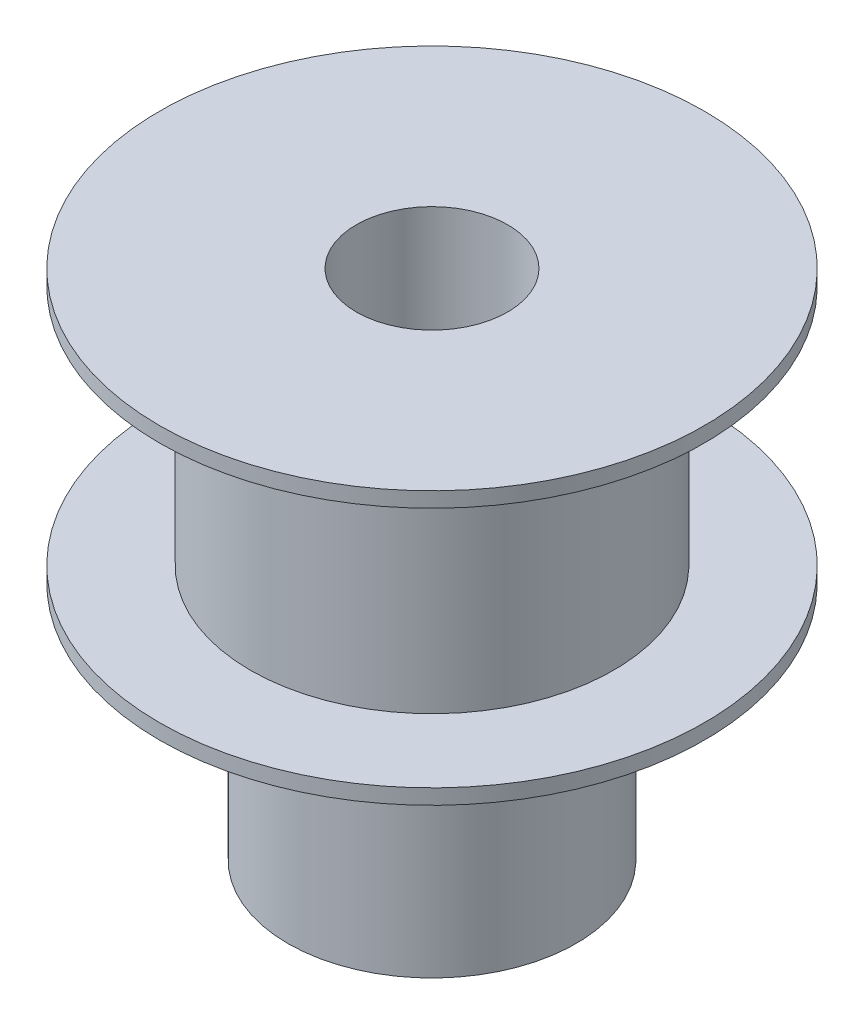
SolidWorks part; units mm, degrees
material "1060 Alloy"
ref_plane "Front Plane" through (0, 0, 0) normal (0, 0, 1) x (1, 0, 0)
ref_plane "Top Plane" through (0, 0, 0) normal (0, 1, 0) x (1, 0, 0)
ref_plane "Right Plane" through (0, 0, 0) normal (1, 0, 0) x (0, 0, -1)
sketch "Sketch1" plane through (0, 0, 0) normal (0, 1, 0) x (1, 0, 0)
  circle A0 centre (0, 0) radius 2.5
  circle A1 centre (0, 0) radius 4.7625
  dimension "D1" = 5
  dimension "D2" = 9.525
extrude "Boss-Extrude1" add sketch "Sketch1" along normal mid plane 7.9375
sketch "Sketch2" plane through (0, 3.9688, 0) normal (0, 1, 0) x (1, 0, 0)
  circle A0 centre (0, 0) radius 2.5
  circle A1 centre (0, 0) radius 9
  circle A2 centre (0, 0) radius 2.5 construction
  dimension "D1" = 18
extrude "Boss-Extrude2" add sketch "Sketch2" along normal blind 9
sketch "Sketch3" plane through (0, 0, 0) normal (1, 0, 0) x (0, 0, -1)
  line L0 (9, 3.9688) -> (9, 12.9688) construction
  line L1 (9, 12.4687) -> (6, 12.4687)
  line L2 (9, 12.4687) -> (9, 4.4688)
  line L3 (9, 4.4688) -> (6, 4.4688)
  line L4 (6, 12.4687) -> (6, 4.4688)
  line L5 (-9, 8.4688) -> (9, 8.4688) construction
  line L6 (-9, 12.9688) -> (-9, 3.9688) construction
  line L7 (9, 12.9688) -> (-9, 12.9688) construction
  point P6 (9, 8.4688)
  dimension "D1" = 0.5
  dimension "D2" = 3
revolve "Cut-Revolve1" cut sketch "Sketch3" angle 360 about axis through (0, 3.9688, 0) along (0, -1, 0)
ref_plane "Plane1" through (0, 8.4688, 0) normal (0, -1, 0) x (-1, 0, 0)
